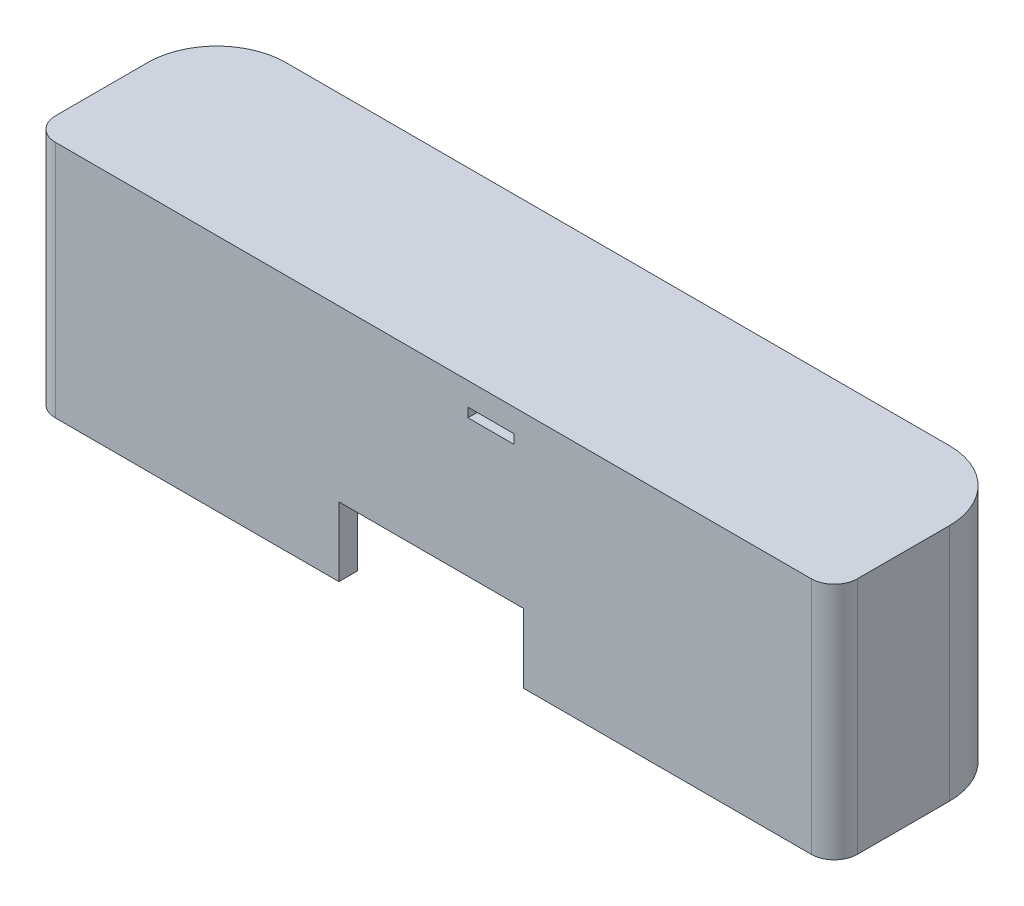
SolidWorks part; units mm, degrees
ref_plane "Front Plane" through (0, 0, 0) normal (0, 0, 1) x (1, 0, 0)
ref_plane "Top Plane" through (0, 0, 0) normal (0, 1, 0) x (1, 0, 0)
ref_plane "Right Plane" through (0, 0, 0) normal (1, 0, 0) x (0, 0, -1)
sketch "Sketch1" plane through (0, 0, 0) normal (0, 1, 0) x (1, 0, 0)
  line L0 (-68.08, 16) -> (68.08, 16)
  line L1 (-82, -20) -> (82, -20)
  line L2 (-87, -15) -> (-87, 5)
  line L3 (-72, 20) -> (72, 20)
  line L4 (87, -15) -> (87, 5)
  line L5 (-87, -20) -> (87, 20) construction
  line L6 (-87, 20) -> (87, -20) construction
  line L7 (-83, -16) -> (83, -16)
  line L11 (-83, -16) -> (82.1569, 15.8375) construction
  line L12 (-81.6467, 15.7391) -> (83, -16) construction
  line L13 (-83, -16) -> (-83, 2.5)
  line L14 (83, -16) -> (83, 2.5)
  arc A1 (87, -15) -> (82, -20) centre (82, -15) cw
  arc A2 (-82, -20) -> (-87, -15) centre (-82, -15) cw
  arc A3 (72, 20) -> (87, 5) centre (72, 5) cw
  arc A4 (-72, 20) -> (-87, 5) centre (-72, 5) ccw
  ellipse E0 centre (-68.08, 2.5) end of major axis (-83, 2.5) minor radius 13.5 (-68.08, 16) -> (-83, 2.5) ccw
  ellipse E2 centre (68.08, 2.5) end of major axis (83, 2.5) minor radius 13.5 (68.08, 16) -> (83, 2.5) cw
  point P0 (0, 0)
  point P1 (0, 0)
  point P3 (0, 0)
  point P6 (0, 0)
  point P12 (0, 0)
  point P13 (0, 0)
  point P22 (0, 0)
  point P24 (0, 0)
  point P44 (68.08, 2.5)
  dimension "D4" = 15
  dimension "D12" = 15
  dimension "D1" = 4
  dimension "D2" = 4
  dimension "D3" = 166
  dimension "D5" = 4
  dimension "D6" = 13.5
  dimension "D7" = 14.92
  dimension "D8" = 14.92
  dimension "D9" = 13.5
  dimension "D10" = 4
  dimension "D11" = 32
extrude "Boss-Extrude1" add sketch "Sketch1" along normal blind 46.8
ref_plane "Plane3" through (0, 0, 20) normal (0, 0, 1) x (1, 0, 0)
sketch "Sketch5" plane through (0, 0, 20) normal (0, 0, 1) x (1, 0, 0)
  line L0 (-82, 0) -> (82, 0) construction
  line L1 (19.5, 15) -> (-20.5, 15)
  line L2 (19.5, 15) -> (19.5, 0)
  line L3 (19.5, 0) -> (-20.5, 0)
  line L4 (-20.5, 15) -> (-20.5, 0)
  line L5 (87, 46.8) -> (87, 0) construction
  dimension "D1" = 40
  dimension "D2" = 15
  dimension "D3" = 67.5
extrude "Cut-Extrude1" cut sketch "Sketch5" against normal up to surface (4 mm away) up to face at (0, 23.4, 16)
ref_plane "Plane5" through (0, 46.8, 0) normal (0, 1, 0) x (1, 0, 0)
sketch "Sketch10" plane through (0, 46.8, 0) normal (0, 1, 0) x (1, 0, 0)
  line L0 (87, -15) -> (87, 5) construction
  line L1 (-82, -20) -> (82, -20)
  line L2 (-87, -15) -> (-87, 5)
  line L3 (-72, 20) -> (72, 20)
  line L4 (87, -15) -> (87, 5)
  line L5 (-87, -20) -> (87, 20) construction
  line L6 (-87, 20) -> (87, -20) construction
  line L7 (72, 20) -> (-72, 20) construction
  arc A0 (72, 20) -> (87, 5) centre (72, 5) cw
  arc A3 (-87, 5) -> (-72, 20) centre (-72, 5) cw
  arc A4 (82, -20) -> (87, -15) centre (82, -15) ccw
  arc A5 (-87, -15) -> (-82, -20) centre (-82, -15) ccw
  point P0 (0, 0)
  point P2 (0, 0)
  point P4 (0, 0)
  point P15 (0, 0)
  point P17 (0, 0)
  point P18 (0, 0)
  dimension "D3" = 15
  dimension "D4" = 5
  dimension "D5" = 5
  dimension "D1" = 0
  dimension "D2" = 0
extrude "Boss-Extrude3" add sketch "Sketch10" along normal blind 5
sketch "Sketch13" plane through (0, 0, 20) normal (0, 0, 1) x (1, 0, 0)
  line L1 (7.5, 46.8) -> (17.5, 46.8)
  line L2 (7.5, 46.8) -> (7.5, 44.8)
  line L3 (7.5, 44.8) -> (17.5, 44.8)
  line L4 (17.5, 46.8) -> (17.5, 44.8)
  line L5 (7.5, 46.8) -> (17.5, 44.8) construction
  line L6 (7.5, 44.8) -> (17.5, 46.8) construction
  line L7 (11, 46.8) -> (-11, 46.8) construction
  line L8 (82, 51.8) -> (82, 0) construction
  point P0 (12.5, 45.8)
  point P5 (0, 0)
  point P6 (0, 0)
  point P9 (0, 0)
  dimension "D1" = 2
  dimension "D2" = 10
  dimension "D3" = 0
  dimension "D4" = 69.5
extrude "Cut-Extrude2" cut sketch "Sketch13" against normal blind 37
equation "\"length\"=138"
